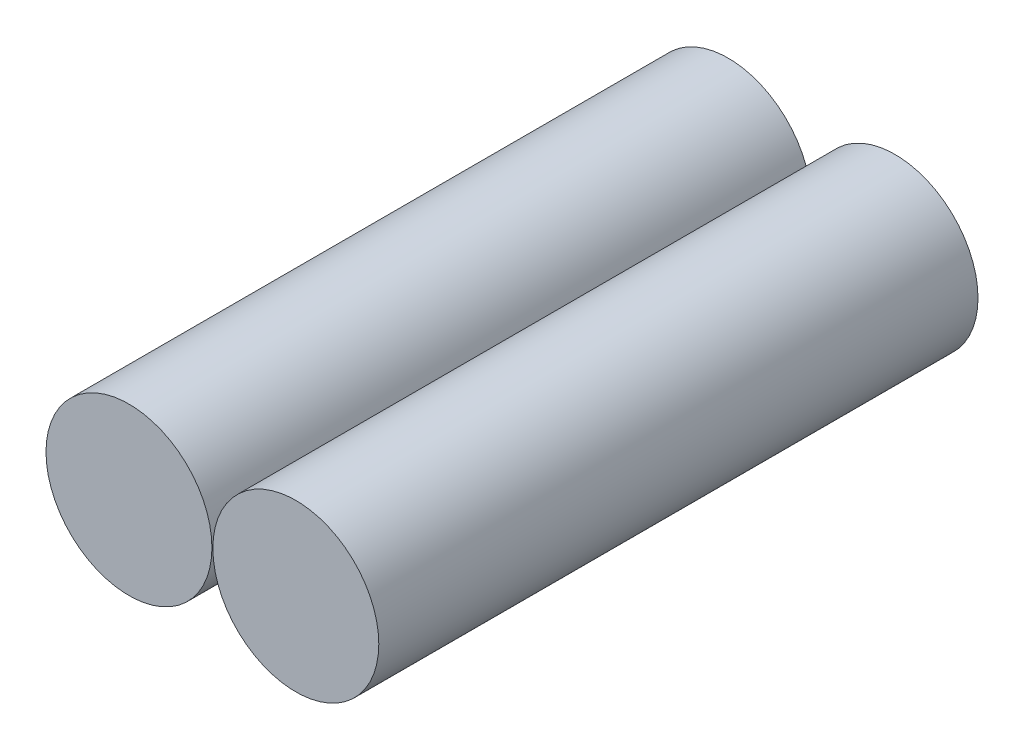
SolidWorks part; units mm, degrees
material "2A12"
ref_plane "前视基准面" through (0, 0, 0) normal (0, 0, 1) x (1, 0, 0)
ref_plane "上视基准面" through (0, 0, 0) normal (0, 1, 0) x (1, 0, 0)
ref_plane "右视基准面" through (0, 0, 0) normal (1, 0, 0) x (0, 0, -1)
sketch "草图1" plane through (0, 0, 0) normal (0, 0, 1) x (1, 0, 0)
  line L0 (18.1, 0) -> (0, 0) construction
  circle A0 centre (0, 0) radius 9
  circle A1 centre (18.1, 0) radius 9
  dimension "D1" = 18
  dimension "D2" = 18.1
extrude "凸台-拉伸1" add sketch "草图1" along normal blind 65
